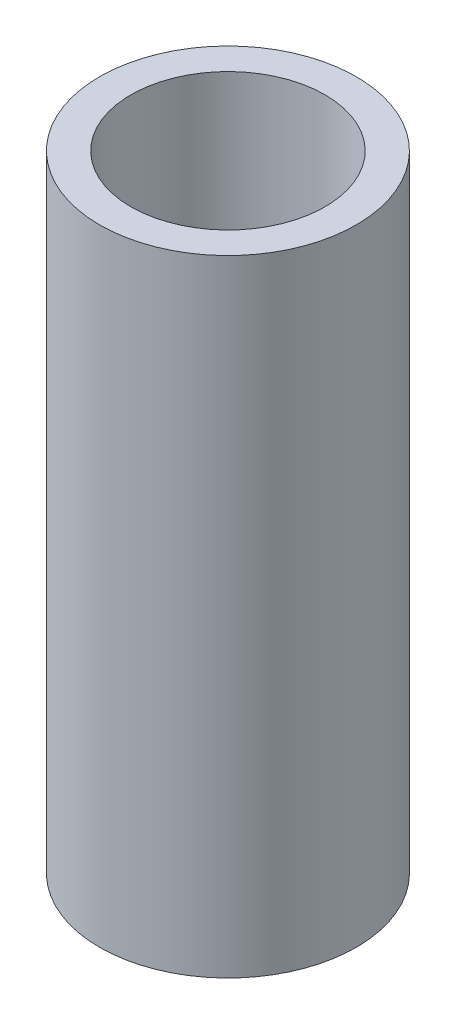
SolidWorks part; units mm, degrees
ref_plane "Front Plane" through (0, 0, 0) normal (0, 0, 1) x (1, 0, 0)
ref_plane "Top Plane" through (0, 0, 0) normal (0, 1, 0) x (1, 0, 0)
ref_plane "Right Plane" through (0, 0, 0) normal (1, 0, 0) x (0, 0, -1)
sketch "Sketch1" plane through (0, 0, 0) normal (0, 1, 0) x (1, 0, 0)
  circle A0 centre (0, 0) radius 3.025
  circle A1 centre (0, 0) radius 4
  dimension "D1" = 6.05
  dimension "D2" = 8
extrude "Boss-Extrude1" add sketch "Sketch1" along normal blind 19.5
